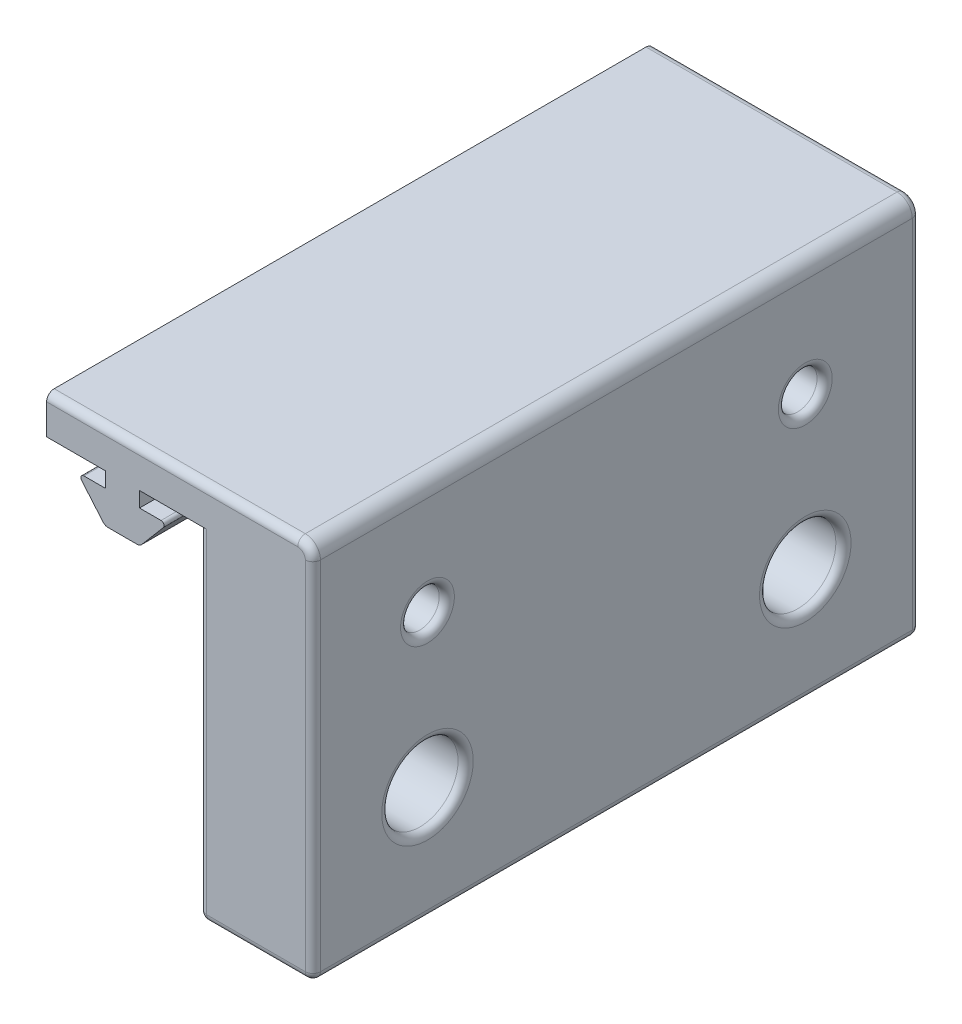
SolidWorks part; units mm, degrees
ref_plane "Front Plane" through (0, 0, 0) normal (0, 0, 1) x (1, 0, 0)
ref_plane "Top Plane" through (0, 0, 0) normal (0, 1, 0) x (1, 0, 0)
ref_plane "Right Plane" through (0, 0, 0) normal (1, 0, 0) x (0, 0, -1)
sketch "Sketch1" plane through (0, 0, 0) normal (0, 0, 1) x (1, 0, 0)
  line L0 (2.8572, 18.7588) -> (2.8513, 16.2188)
  line L1 (-12.827, 18.7588) -> (12.827, 18.7588)
  line L2 (-12.827, 18.7588) -> (-12.827, 25.1088)
  line L3 (-12.827, 25.1088) -> (12.827, 25.1088)
  line L4 (12.827, 18.7588) -> (12.827, 25.1088)
  line L5 (-12.827, 18.7588) -> (12.827, 25.1088) construction
  line L6 (-12.827, 25.1088) -> (12.827, 18.7588) construction
  line L9 (-2.921, 10.7578) -> (2.921, 10.7578)
  line L11 (-7.5568, 16.2188) -> (-2.8519, 16.2188)
  line L12 (2.8543, 17.4888) -> (-2.8543, 17.4888) construction
  line L13 (-7.5568, 16.2188) -> (-2.921, 10.7578)
  line L15 (-2.8567, 18.7588) -> (-2.8519, 16.2188)
  line L16 (7.5562, 16.2188) -> (2.921, 10.7578)
  line L17 (2.8513, 16.2188) -> (7.5562, 16.2188)
  point P0 (0, 21.9338)
  point P5 (0, 10.7578)
  point P7 (0, 18.7588)
  point P14 (0, 16.2188)
  point P19 (0, 17.4888)
  dimension "D1" = 6.35
  dimension "D2" = 5.842
  dimension "D3" = 8.001
  dimension "D4" = 15.113
  dimension "D5" = 2.54
  dimension "D6" = 25.654
extrude "Boss-Extrude1" add sketch "Sketch1" along normal blind 101.6 contours L1 L4 L3 L2 | L17 L0 L1 L15 L11 L13 L9 L16
fillet "Fillet1" radius 0.508 2 edges at (7.5562, 16.2188, 50.8) (-7.5568, 16.2188, 50.8)
fillet "Fillet2" radius 1.016 2 edges at (2.921, 10.7578, 50.8) (-2.921, 10.7578, 50.8)
sketch "Sketch3" plane through (0, 0, 0) normal (0, 0, -1) x (-1, 0, 0)
  line L1 (-12.827, 25.1088) -> (-31.877, 25.1088)
  line L2 (-12.827, 25.1088) -> (-12.827, -38.3912)
  line L3 (-12.827, -38.3912) -> (-31.877, -38.3912)
  line L4 (-31.877, 25.1088) -> (-31.877, -38.3912)
  dimension "D1" = 19.05
  dimension "D2" = 63.5
extrude "Boss-Extrude3" add sketch "Sketch3" against normal up to surface (101.6 mm away) up to face at (-0.0001, 16.5448, 101.6)
sketch "Sketch4" plane through (31.877, 0, 0) normal (1, 0, 0) x (0, 0, -1)
  line L0 (-101.6, 25.1088) -> (0, 25.1088) construction
  line L2 (-101.6, -19.3412) -> (0, -19.3412) construction
  line L3 (0, 25.1088) -> (0, -38.3912) construction
  line L5 (-82.423, -19.3412) -> (-19.177, -19.3412)
  circle A0 centre (-19.177, -19.3412) radius 6.3881
  circle A1 centre (-82.423, -19.3412) radius 6.3881
  point P3 (0, 0)
  point P11 (-50.8, -19.3412)
  dimension "D3" = 12.7762
  dimension "D1" = 44.45
  dimension "D2" = 63.246
extrude "Cut-Extrude1" cut sketch "Sketch4" against normal blind 25.4
fillet "Fillet3" radius 2.54 1 edges at (31.877, 25.1088, 50.8)
fillet "Fillet4" radius 1.27 2 edges at (31.877, -12.9531, 82.423) (31.877, -12.9531, 19.177)
fillet "Fillet5" radius 1.27 12 edges at (8.255, 25.1088, 0) (31.1331, 24.3648, 0) (8.255, 25.1088, 101.6) (31.1331, 24.3648, 101.6) (12.827, -9.8162, 101.6) (12.827, -9.8162, 0) (12.827, -38.3912, 50.8) (22.352, -38.3912, 101.6) (22.352, -38.3912, 0) (31.877, -38.3912, 50.8) (31.877, -7.9112, 0) (31.877, -7.9112, 101.6)
sketch "Sketch5" plane through (31.877, 0, 0) normal (1, 0, 0) x (0, 0, -1)
  line L0 (-82.423, 6.0588) -> (-19.177, 6.0588) construction
  line L4 (-100.33, -37.1212) -> (-1.27, -37.1212) construction
  line L5 (-100.33, 25.1088) -> (-1.27, 25.1088) construction
  circle A2 centre (-82.423, 6.0588) radius 3.2385
  circle A3 centre (-19.177, 6.0588) radius 3.2385
  point P12 (-50.8, -37.1212)
  dimension "D2" = 6.477
  dimension "D1" = 6.477
  dimension "D3" = 19.05
  dimension "D4" = 63.246
extrude "Cut-Extrude3" cut sketch "Sketch5" against normal up to next
fillet "Fillet7" radius 1.27 2 edges at (31.877, 9.2973, 19.177) (31.877, 9.2973, 82.423)
sketch "Sketch6" plane through (0, 0, 101.6) normal (0, 0, 1) x (1, 0, 0)
  line L0 (-12.827, 18.7588) -> (-2.8567, 18.7588) construction
  line L1 (-12.827, 25.1088) -> (-12.7, 25.1088)
  line L2 (-12.827, 25.1088) -> (-12.827, 18.7588)
  line L3 (-12.827, 18.7588) -> (-12.7, 18.7588)
  line L4 (-12.7, 25.1088) -> (-12.7, 18.7588)
  dimension "D1" = 0.127
extrude "Cut-Extrude4" cut sketch "Sketch6" against normal through all
